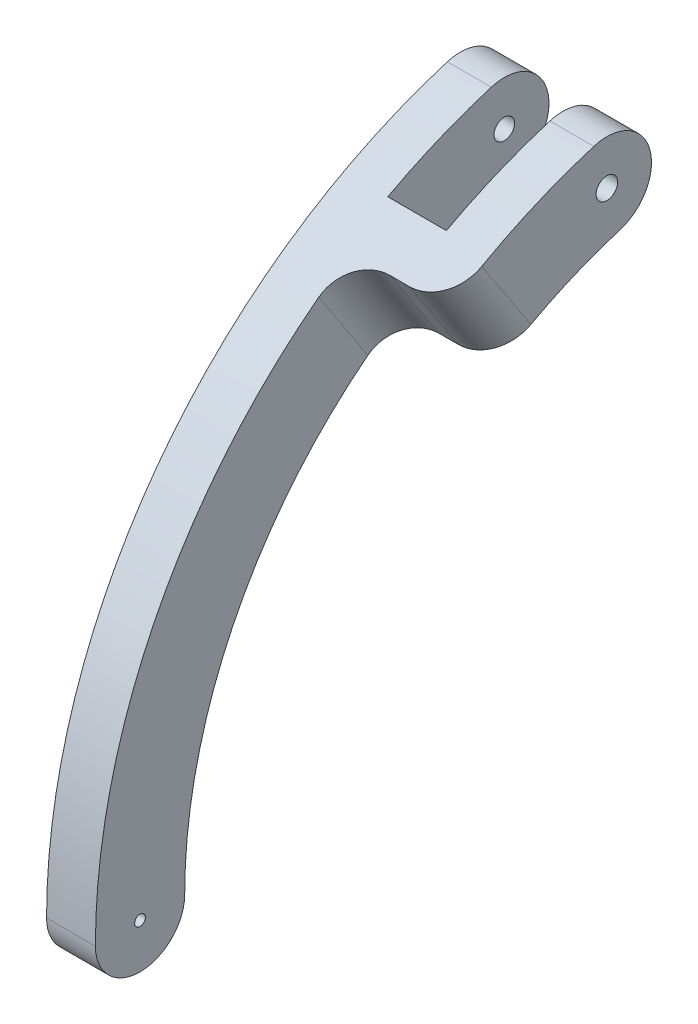
SolidWorks part; units mm, degrees
material "ABS"
ref_plane "Front Plane" through (0, 0, 0) normal (0, 0, 1) x (1, 0, 0)
ref_plane "Top Plane" through (0, 0, 0) normal (0, 1, 0) x (1, 0, 0)
ref_plane "Right Plane" through (0, 0, 0) normal (1, 0, 0) x (0, 0, -1)
sketch "Esquisse1" plane through (0, 0, 0) normal (1, 0, 0) x (0, 0, -1)
  arc A0 (-48.768, 0) -> (-14.2102, 46.6518) centre (0, 0) cw
  arc A1 (-57.912, 0) -> (-16.8746, 55.399) centre (0, 0) cw
  arc A2 (-57.912, 0) -> (-48.768, 0) centre (-53.34, 0) ccw
  arc A3 (-14.2102, 46.6518) -> (-16.8746, 55.399) centre (-15.5424, 51.0254) ccw
  circle A4 centre (-53.34, 0) radius 0.55
  circle A5 centre (-15.5424, 51.0254) radius 1.05
  dimension "D1" = 4.572
  dimension "D4" = 1.1
  dimension "D5" = 2.1
  dimension "D2" = 63.5
  dimension "D3" = 53.34
extrude "Boss.-Extru.1" add sketch "Esquisse1" along normal blind 5
sketch "Esquisse2" plane through (5, 0, 0) normal (1, 0, 0) x (0, 0, -1)
  line L0 (-31.7726, 48.418) -> (-26.7559, 40.773)
  arc A0 (-14.2102, 46.6518) -> (-48.768, 0) centre (0, 0) ccw construction
  arc A1 (-16.8746, 55.399) -> (-57.912, 0) centre (0, 0) ccw construction
  arc A2 (-14.2102, 46.6518) -> (-16.8746, 55.399) centre (-15.5424, 51.0254) ccw construction
  arc A3 (-14.2102, 46.6518) -> (-26.7559, 40.773) centre (0, 0) ccw
  arc A4 (-16.8746, 55.399) -> (-31.7726, 48.418) centre (0, 0) ccw
  arc A5 (-14.2102, 46.6518) -> (-16.8746, 55.399) centre (-15.5424, 51.0254) ccw
  dimension "D1" = 15
extrude "Boss.-Extru.2" add sketch "Esquisse2" along normal blind 10
ref_plane "Plan1" through (0, 48.418, 31.7726) normal (0, 0.8361, 0.5486) x (-1, 0, 0)
sketch "Esquisse3" plane through (0, 48.418, 31.7726) normal (0, 0.8361, 0.5486) x (-1, 0, 0)
  line L0 (0, -16.2857) -> (0, 48.418) construction
  line L1 (-4.5, -21.0693) -> (-10.5, -21.0693)
  line L2 (-4.5, -21.0693) -> (-4.5, -5)
  line L3 (-4.5, -5) -> (-10.5, -5)
  line L4 (-10.5, -21.0693) -> (-10.5, -5)
  line L6 (-15, 0) -> (-5, 0) construction
  line L9 (-15, 0) -> (-15, -16.2857) construction
  dimension "D1" = 4.5
  dimension "D2" = 4.5
  dimension "D3" = 5
extrude "Enlèv. mat.-Extru.1" cut sketch "Esquisse3" against normal through all and the other way through all
fillet "Congé1" radius 4 2 edges at (5, 44.5955, 29.2643) (15, 44.5955, 29.2643)
sketch "Esquisse4" plane through (10.5, 0, 0) normal (-1, 0, 0) x (0, 0, 1)
  circle A0 centre (15.5424, 51.0254) radius 1.1
  dimension "D1" = 2.2
extrude "Enlèv. mat.-Extru.2" cut sketch "Esquisse4" against normal through all
